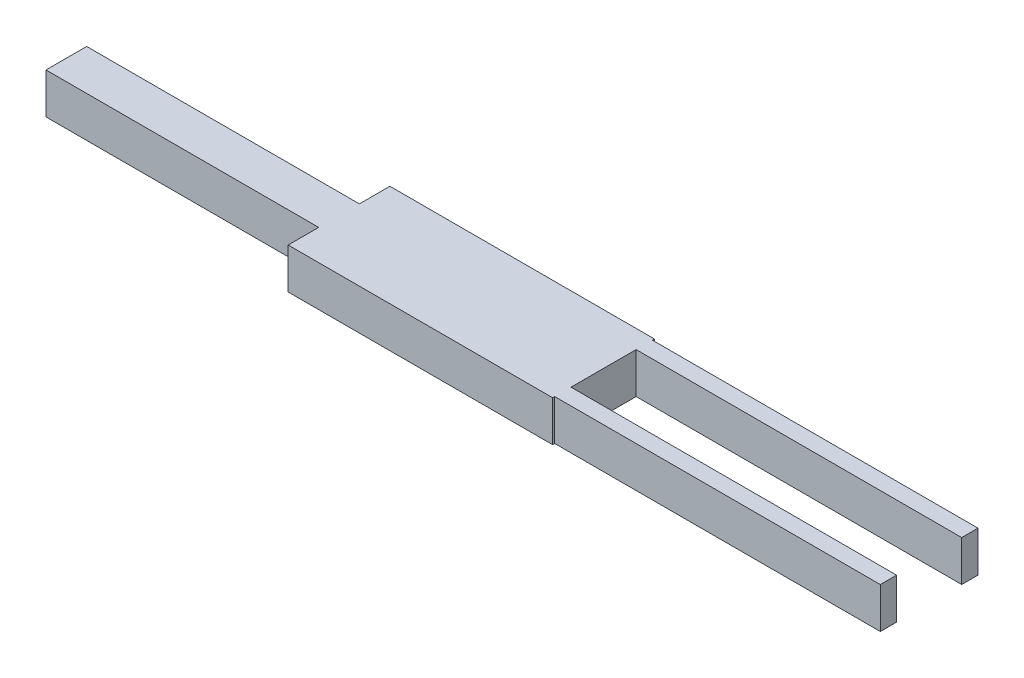
SolidWorks part; units mm, degrees
ref_plane "Front Plane" through (0, 0, 0) normal (0, 0, 1) x (1, 0, 0)
ref_plane "Top Plane" through (0, 0, 0) normal (0, 1, 0) x (1, 0, 0)
ref_plane "Right Plane" through (0, 0, 0) normal (1, 0, 0) x (0, 0, -1)
sketch "Sketch1" plane through (0, 0, 0) normal (0, 1, 0) x (1, 0, 0)
  line L0 (251.1979, 10.1864) -> (171.1979, 10.1864)
  line L1 (171.1979, 10.1864) -> (171.1979, -5.8136)
  line L2 (171.1979, -5.8136) -> (251.1979, -5.8136)
  line L3 (251.1979, 10.1864) -> (251.1979, 14.1864)
  line L12 (39.1979, -2.8136) -> (106.1979, -2.8136)
  line L16 (106.1979, -2.8136) -> (106.1979, -10.3136)
  line L17 (106.1979, -10.3136) -> (171.1979, -10.3136)
  line L18 (171.1979, -10.3136) -> (171.1979, -9.8136)
  line L19 (171.1979, -9.8136) -> (251.1979, -9.8136)
  line L20 (251.1979, -9.8136) -> (251.1979, -5.8136)
  line L21 (251.1979, 14.1864) -> (171.1979, 14.1864)
  line L22 (171.1979, 14.1864) -> (171.1979, 14.6864)
  line L23 (171.1979, 14.6864) -> (106.1979, 14.6864)
  line L24 (106.1979, 14.6864) -> (106.1979, 7.1864)
  line L25 (106.1979, 7.1864) -> (39.1979, 7.1864)
  line L26 (39.1979, 7.1864) -> (39.1979, -2.8136)
  dimension "D2" = 4
  dimension "D3" = 67
  dimension "D9" = 10
  dimension "D10" = 65
  dimension "D11" = 25
  dimension "D12" = 80
  dimension "D13" = 24
extrude "Boss-Extrude1" add sketch "Sketch1" along normal blind 10
